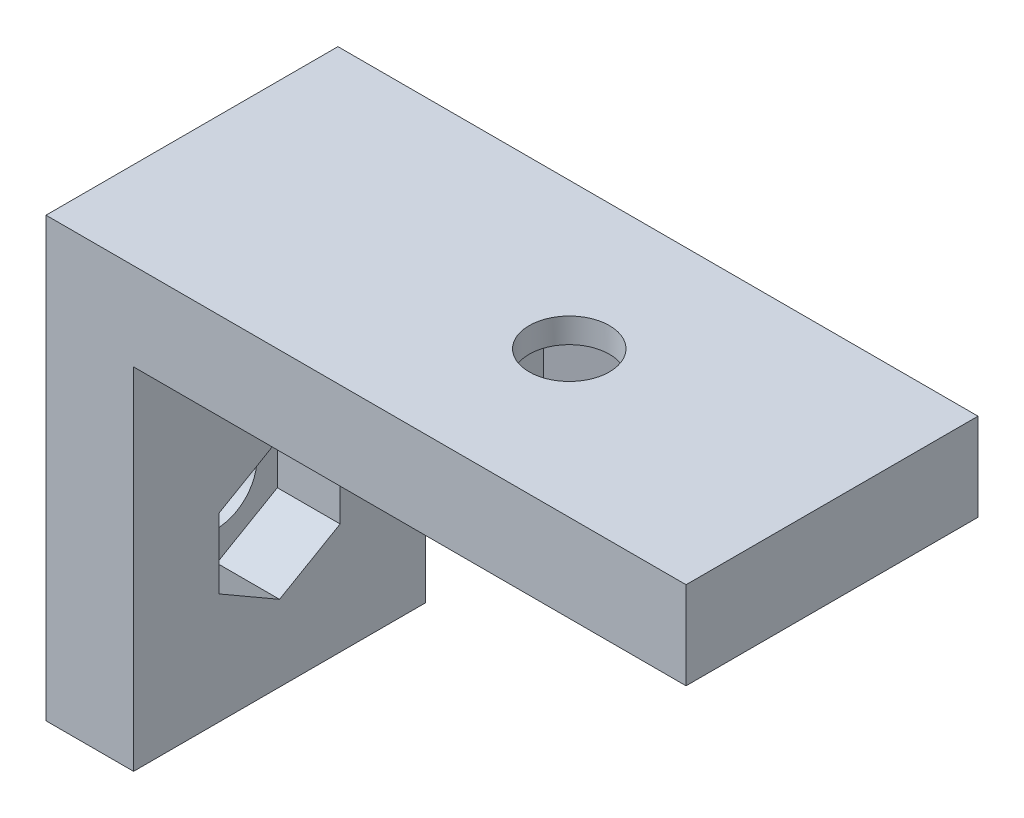
SolidWorks part; units mm, degrees
ref_plane "Спереди" through (0, 0, 0) normal (0, 0, 1) x (1, 0, 0)
ref_plane "Сверху" through (0, 0, 0) normal (0, 1, 0) x (1, 0, 0)
ref_plane "Справа" through (0, 0, 0) normal (1, 0, 0) x (0, 0, -1)
other "Configuration Table"
sketch "Профиль_скобы_6мм" plane through (0, 0, 0) normal (0, 0, 1) x (1, 0, 0)
  line L0 (6.15, -30) -> (12.15, -30)
  line L1 (12.15, -30) -> (12.15, -6)
  line L2 (12.15, -6) -> (50, -6)
  line L3 (50, -6) -> (50, 0)
  line L4 (50, 0) -> (6.15, 0)
  line L5 (6.15, 0) -> (6.15, -30)
  dimension "X001" = 6.15
  dimension "X002" = 12.15
  dimension "X003" = 50
  dimension "Y001" = 30
  dimension "Y002" = 6
extrude "Печатный_корпус_20мм" add sketch "Профиль_скобы_6мм" along normal blind 20
sketch "Винты_полки_М5_эскиз" plane through (0, 0, 0) normal (0, 1, 0) x (1, 0, 0)
  circle A0 centre (32, -10) radius 2.75
  dimension "Диаметр001" = 5.5
  dimension "X001" = 32
  dimension "Y001" = 10
extrude "Винты_полки_М5" cut sketch "Винты_полки_М5_эскиз" against normal through all and the other way through all
sketch "Гайки_полки_М5_эскиз" plane through (0, -6, 0) normal (0, -1, 0) x (1, 0, 0)
  line L0 (32, 14.792) -> (36.15, 12.396)
  line L1 (36.15, 12.396) -> (36.15, 7.604)
  line L2 (36.15, 7.604) -> (32, 5.208)
  line L3 (32, 5.208) -> (27.85, 7.604)
  line L4 (27.85, 7.604) -> (27.85, 12.396)
  line L5 (27.85, 12.396) -> (32, 14.792)
  dimension "X001" = 27.85
  dimension "X002" = 32
  dimension "X003" = 36.15
  dimension "Y001" = 5.208
  dimension "Y002" = 7.604
  dimension "Y003" = 12.396
  dimension "Y004" = 14.792
extrude "Гайки_полки_М5_4_3мм" cut sketch "Гайки_полки_М5_эскиз" against normal blind 4.3
sketch "Винт_рамки_М5_эскиз" plane through (0, 0, 0) normal (1, 0, 0) x (0, 0, -1)
  circle A0 centre (-10, -20) radius 2.75
  dimension "Диаметр001" = 5.5
  dimension "X001" = 10
  dimension "Y001" = 20
extrude "Винт_рамки_М5" cut sketch "Винт_рамки_М5_эскиз" against normal through all and the other way through all
sketch "Гайка_рамки_М5_эскиз" plane through (12.15, 0, 0) normal (1, 0, 0) x (0, 0, -1)
  line L0 (-10, -15.208) -> (-14.15, -17.604)
  line L1 (-14.15, -17.604) -> (-14.15, -22.396)
  line L2 (-14.15, -22.396) -> (-10, -24.792)
  line L3 (-10, -24.792) -> (-5.85, -22.396)
  line L4 (-5.85, -22.396) -> (-5.85, -17.604)
  line L5 (-5.85, -17.604) -> (-10, -15.208)
  dimension "X001" = 14.15
  dimension "X002" = 10
  dimension "X003" = 5.85
  dimension "Y001" = 24.792
  dimension "Y002" = 22.396
  dimension "Y003" = 17.604
  dimension "Y004" = 15.208
extrude "Гайка_рамки_М5_4_3мм" cut sketch "Гайка_рамки_М5_эскиз" against normal blind 4.3
